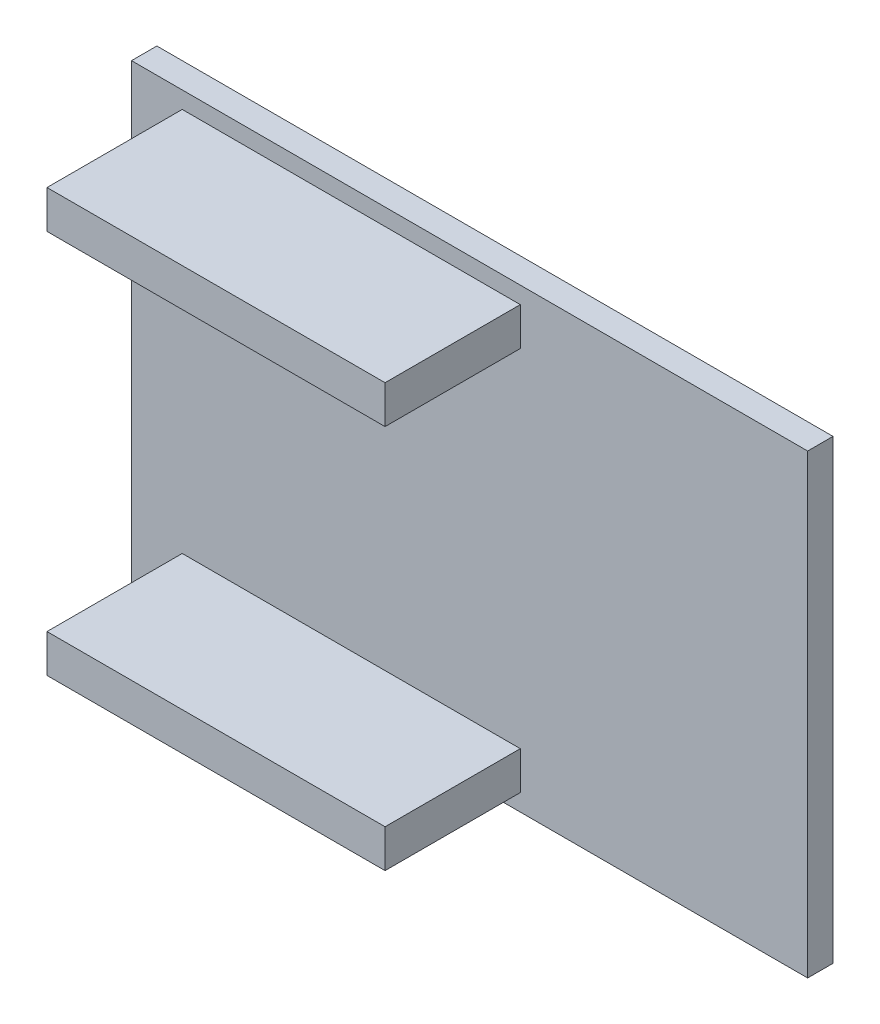
SolidWorks part; units mm, degrees
ref_plane "Front Plane" through (0, 0, 0) normal (0, 0, 1) x (1, 0, 0)
ref_plane "Top Plane" through (0, 0, 0) normal (0, 1, 0) x (1, 0, 0)
ref_plane "Right Plane" through (0, 0, 0) normal (1, 0, 0) x (0, 0, -1)
sketch "Sketch1" plane through (0, 0, 0) normal (0, 0, 1) x (1, 0, 0)
  line L0 (0, 26.2212) -> (0, -26.0481) construction
  line L1 (-39.1154, 0) -> (30.4615, 0) construction
  line L2 (20, 13.5) -> (-20, 13.5)
  line L3 (-20, 13.5) -> (-20, -13.5)
  line L4 (20, -13.5) -> (-20, -13.5)
  line L5 (20, 13.5) -> (20, -13.5)
  point P9 (-20, 0)
  point P10 (20, 0)
  point P12 (0, -13.5)
  point P13 (0, 13.5)
  dimension "D1" = 27
  dimension "D2" = 40
extrude "Boss-Extrude1" add sketch "Sketch1" along normal blind 1.5
sketch "Sketch2" plane through (0, 0, 1.5) normal (0, 0, 1) x (1, 0, 0)
  line L0 (-30.4065, 0) -> (28.4581, 0) construction
  line L1 (0, 19.0114) -> (0, -22.9082) construction
  line L2 (-17, 12.5) -> (-17, 10.25)
  line L3 (-17, 10.25) -> (3, 10.25)
  line L4 (3, 10.25) -> (3, 12.5)
  line L5 (3, 12.5) -> (-17, 12.5)
  line L6 (3, -12.5) -> (-17, -12.5)
  line L7 (3, -10.25) -> (3, -12.5)
  line L8 (-17, -10.25) -> (3, -10.25)
  line L9 (-17, -12.5) -> (-17, -10.25)
  line L10 (-20, 13.5) -> (-20, -13.5) construction
  dimension "D1" = 25
  dimension "D2" = 3
  dimension "D3" = 20
  dimension "D4" = 2.25
extrude "Boss-Extrude2" add sketch "Sketch2" along normal blind 8
